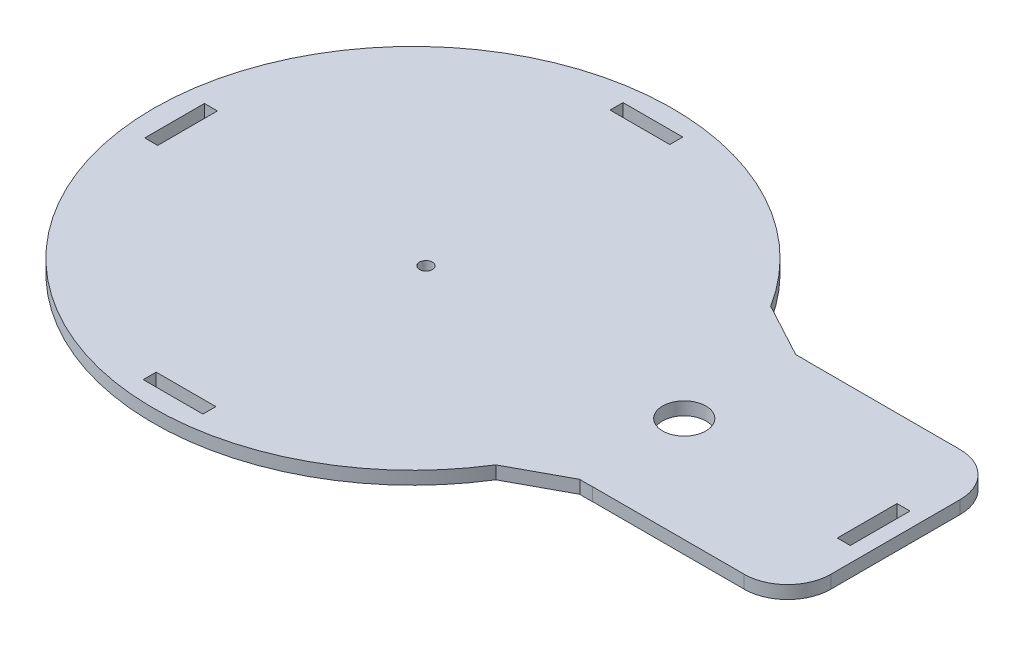
SolidWorks part; units mm, degrees
ref_plane "Спереди" through (0, 0, 0) normal (0, 0, 1) x (1, 0, 0)
ref_plane "Сверху" through (0, 0, 0) normal (0, 1, 0) x (1, 0, 0)
ref_plane "Справа" through (0, 0, 0) normal (1, 0, 0) x (0, 0, -1)
other "Configuration Table"
sketch "Эскиз2" plane through (0, 0, 0) normal (0, 1, 0) x (1, 0, 0)
  line L0 (50.9013, -31.7657) -> (63.5214, -24.9562)
  line L1 (0, 0) -> (65, 0) construction
  line L2 (50.9013, 31.7657) -> (63.5214, 24.9562)
  arc A0 (50.9013, 31.7657) -> (50.9013, -31.7657) centre (0, 0) ccw
  arc A1 (63.5214, -24.9562) -> (63.5214, 24.9562) centre (65, 0) ccw
  dimension "D1" = 120
  dimension "D2" = 50
  dimension "D3" = 65
extrude "Бобышка-Вытянуть1" add sketch "Эскиз2" along normal blind 3
sketch "Эскиз3" plane through (0, 3, 0) normal (0, 1, 0) x (1, 0, 0)
  line L0 (0, -64.6867) -> (0, 64.6867) construction
  line L1 (-104.0068, 0) -> (104.0068, 0) construction
  line L2 (-6.9, 52.4569) -> (6.9, 52.4569)
  line L3 (-6.9, -55.4569) -> (6.9, -55.4569)
  line L4 (-6.9, -55.4569) -> (-6.9, -52.4569)
  line L5 (-6.9, -52.4569) -> (6.9, -52.4569)
  line L6 (6.9, -55.4569) -> (6.9, -52.4569)
  line L7 (-6.9, -55.4569) -> (6.9, -52.4569) construction
  line L8 (-6.9, -52.4569) -> (6.9, -55.4569) construction
  line L9 (6.9, 55.4569) -> (6.9, 52.4569)
  line L10 (-6.9, 55.4569) -> (6.9, 55.4569)
  line L11 (-6.9, 55.4569) -> (-6.9, 52.4569)
  line L13 (-55.1052, -6.9) -> (-52.1052, -6.9)
  line L14 (-55.1052, -6.9) -> (-55.1052, 6.9)
  line L15 (-55.1052, 6.9) -> (-52.1052, 6.9)
  line L16 (-52.1052, -6.9) -> (-52.1052, 6.9)
  line L17 (-55.1052, -6.9) -> (-52.1052, 6.9) construction
  line L18 (-55.1052, 6.9) -> (-52.1052, -6.9) construction
  point P0 (0, -53.9569)
  point P5 (0, 0)
  point P10 (0, 0)
  point P15 (-53.6052, 0)
  point P25 (-59.6735, 0)
  point P27 (90.0559, 0)
  dimension "D1" = 3
  dimension "D2" = 13.8
  dimension "D3" = 13.8
  dimension "D4" = 3
extrude "Вырез-Вытянуть1" cut sketch "Эскиз3" against normal blind 10
sketch "Эскиз5" plane through (0, 3, 0) normal (0, 1, 0) x (1, 0, 0)
  line L1 (63.5214, 24.9562) -> (111.5214, 24.9562)
  line L2 (63.5214, 24.9562) -> (63.5214, -24.9562)
  line L3 (63.5214, -24.9562) -> (111.5214, -24.9562)
  line L4 (111.5214, 24.9562) -> (111.5214, -24.9562)
  arc A0 (63.5214, -24.9562) -> (63.5214, 24.9562) centre (65, 0) ccw construction
  arc A1 (63.5214, -24.9562) -> (66.4786, -24.9562) centre (65, 0) ccw
  arc A2 (66.4786, 24.9562) -> (63.5214, 24.9562) centre (65, 0) ccw
  dimension "D1" = 48
extrude "Бобышка-Вытянуть2" add sketch "Эскиз5" against normal up to surface (3 mm away) up to face at (0, 0, 53.9569)
fillet "Скругление1" radius 10 2 edges at (111.5214, 1.5, -24.9562) (111.5214, 1.5, 24.9562)
sketch "Эскиз6" plane through (0, 3, 0) normal (0, 1, 0) x (1, 0, 0)
  line L0 (66.4786, 24.9562) -> (101.5214, 24.9562) construction
  line L1 (108.0214, -6.9438) -> (105.0214, -6.9438)
  line L2 (108.0214, -6.9438) -> (108.0214, 6.8562)
  line L3 (108.0214, 6.8562) -> (105.0214, 6.8562)
  line L4 (105.0214, -6.9438) -> (105.0214, 6.8562)
  line L5 (108.0214, -6.9438) -> (105.0214, 6.8562) construction
  line L6 (108.0214, 6.8562) -> (105.0214, -6.9438) construction
  line L7 (111.5214, 14.9562) -> (111.5214, -14.9562) construction
  point P0 (106.5214, -0.0438)
  dimension "D1" = 3
  dimension "D2" = 13.8
  dimension "D3" = 25
  dimension "D4" = 5
extrude "Вырез-Вытянуть2" cut sketch "Эскиз6" against normal blind 10
sketch "Эскиз7" plane through (0, 3, 0) normal (0, 1, 0) x (1, 0, 0)
  circle A1 centre (3, 0) radius 1.5
  dimension "D2" = 3
extrude "Вырез-Вытянуть3" cut sketch "Эскиз7" against normal blind 10 contours A1
sketch "Эскиз8" plane through (0, 3, 0) normal (0, 1, 0) x (1, 0, 0)
  line L0 (111.5214, 14.9562) -> (111.5214, -14.9562) construction
  line L1 (66.4786, 24.9562) -> (101.5214, 24.9562) construction
  circle A0 centre (63.4014, -0.7038) radius 5
  dimension "D1" = 10
  dimension "D2" = 48.12
  dimension "D3" = 25.66
extrude "Вырез-Вытянуть4" cut sketch "Эскиз8" against normal blind 10
